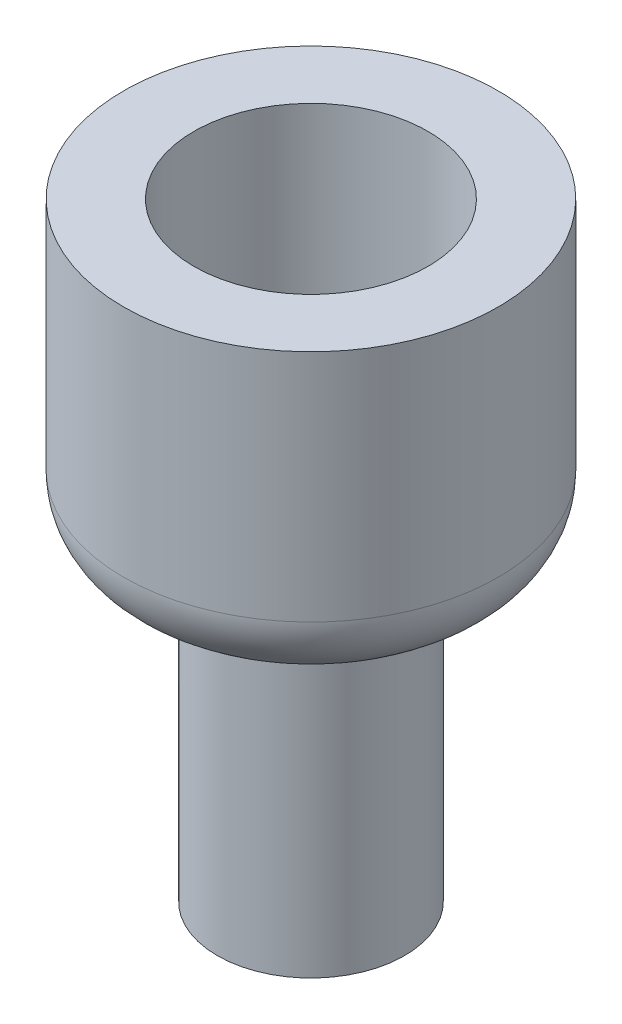
SolidWorks part; units mm, degrees
material "Brass"
ref_plane "Front Plane" through (0, 0, 0) normal (0, 0, 1) x (1, 0, 0)
ref_plane "Top Plane" through (0, 0, 0) normal (0, 1, 0) x (1, 0, 0)
ref_plane "Right Plane" through (0, 0, 0) normal (1, 0, 0) x (0, 0, -1)
sketch "Sketch1" plane through (0, 0, 0) normal (0, 0, 1) x (1, 0, 0)
  line L0 (0, 0) -> (-4230.5367, 0) construction
  line L1 (0, 0) -> (0, -4230.5367) construction
  line L2 (-2.5, 0) -> (-2, 0)
  line L3 (-2, 0) -> (-2, -6.5)
  line L4 (-2, -6.5) -> (-0.75, -6.5)
  line L5 (-0.75, -6.5) -> (-0.75, 1.5)
  line L6 (-0.75, 1.5) -> (-2.5, 2.5104)
  line L7 (-2.5, 2.5104) -> (-2.5, 6.5)
  line L8 (-2.5, 6.5) -> (-4, 6.5)
  line L9 (-4, 6.5) -> (-4, 1.5)
  arc A0 (-4, 1.5) -> (-2.5, 0) centre (-2.5, 1.5) ccw
  point P15 (0, 0)
  point P16 (-5.3008, 1.0228)
  point P17 (0, 0)
  point P18 (0, 0)
  point P19 (0, 0)
  point P20 (-2.5, 1.419)
  point P21 (0, 0)
  point P22 (-2.5, 2.7634)
  dimension "D1" = 6.5
  dimension "D2" = 6.5
  dimension "D3" = 1.5
  dimension "D4" = 4
  dimension "D5" = 5
  dimension "D6" = 8
  dimension "D7" = 5
  dimension "D8" = 30
revolve "Revolve1" add sketch "Sketch1" angle 360 about L1
cosmetic thread "Cosmetic Thread1" parameters "D2"=3.22
